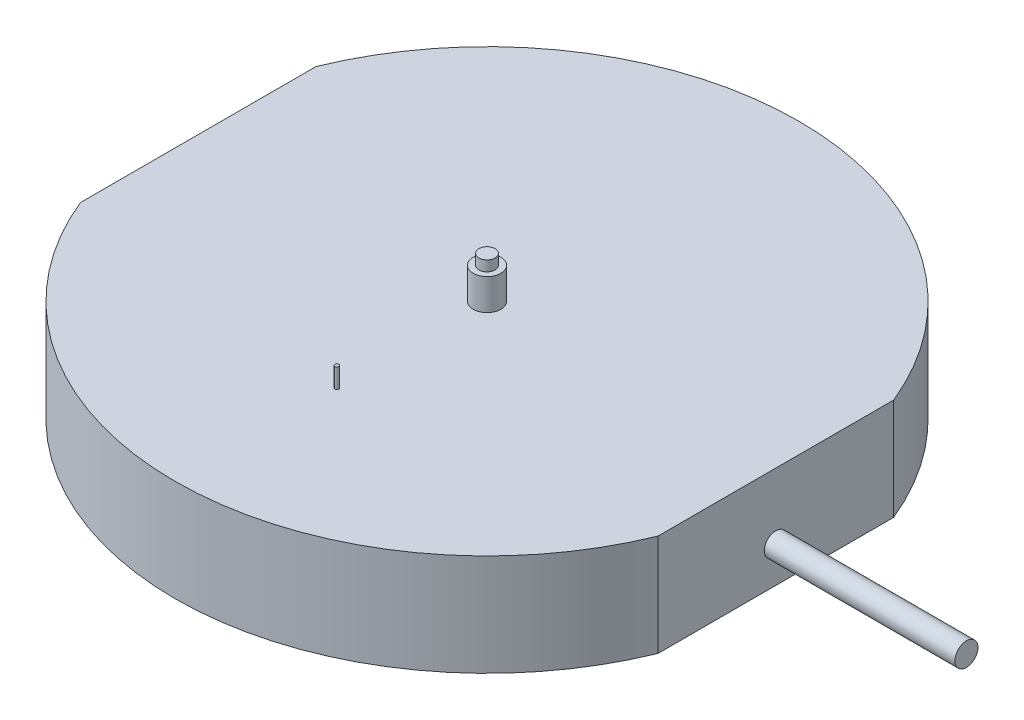
SolidWorks part; units mm, degrees
ref_plane "Front Plane" through (0, 0, 0) normal (0, 0, 1) x (1, 0, 0)
ref_plane "Top Plane" through (0, 0, 0) normal (0, 1, 0) x (1, 0, 0)
ref_plane "Right Plane" through (0, 0, 0) normal (1, 0, 0) x (0, 0, -1)
sketch "Sketch1" plane through (0, 0, 0) normal (0, 1, 0) x (1, 0, 0)
  circle A0 centre (0, 0) radius 13.5
extrude "Boss-Extrude1" add sketch "Sketch1" along normal blind 4.4 contours A0
sketch "Sketch2" plane through (0, 0, 0) normal (0, 1, 0) x (1, 0, 0)
  line L5 (-12.5, -15) -> (-24.1856, -15)
  line L6 (-12.5, -15) -> (-12.5, 15)
  line L7 (-12.5, 15) -> (-24.1856, 15)
  line L8 (-24.1856, -15) -> (-24.1856, 15)
  line L9 (12.5, 15) -> (18.7093, 15)
  line L10 (12.5, 15) -> (12.5, -15)
  line L11 (12.5, -15) -> (18.7093, -15)
  line L12 (18.7093, 15) -> (18.7093, -15)
extrude "Cut-Extrude2" cut sketch "Sketch2" along normal blind 4.4
sketch "Sketch3" plane through (0, 4.4, 0) normal (0, 1, 0) x (1, 0, 0)
  circle A0 centre (0, 0) radius 0.6
extrude "Boss-Extrude2" add sketch "Sketch3" along normal blind 1.35
sketch "Sketch4" plane through (0, 5.75, 0) normal (0, 1, 0) x (1, 0, 0)
  circle A0 centre (0, 0) radius 0.35
extrude "Boss-Extrude3" add sketch "Sketch4" along normal blind 0.45
sketch "Sketch5" plane through (12.5, 0, 0) normal (1, 0, 0) x (0, 0, -1)
  circle A0 centre (0, 1.55) radius 0.5
extrude "Boss-Extrude4" add sketch "Sketch5" along normal blind 8.25
sketch "Sketch7" plane through (0, 4.4, 0) normal (0, 1, 0) x (1, 0, 0)
  circle A0 centre (0, -6.5) radius 0.085
extrude "Boss-Extrude5" add sketch "Sketch7" along normal blind 0.85
